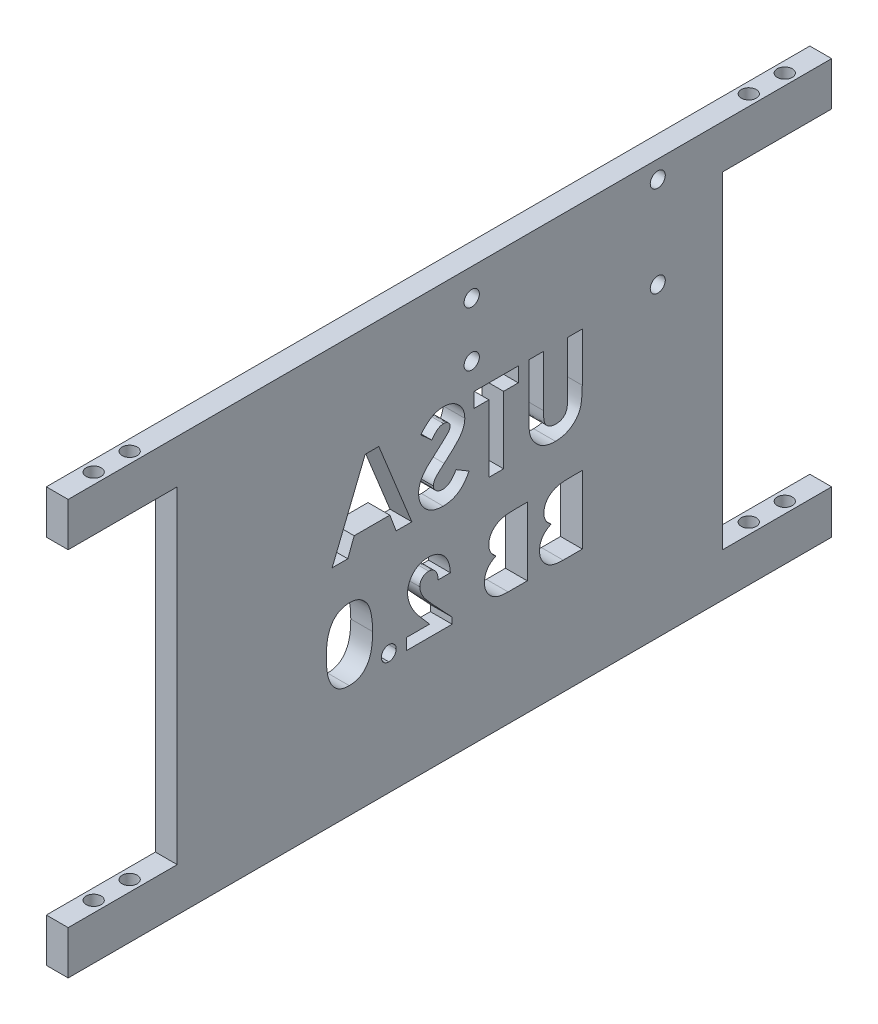
SolidWorks part; units mm, degrees
ref_plane "Front Plane" through (0, 0, 0) normal (0, 0, 1) x (1, 0, 0)
ref_plane "Top Plane" through (0, 0, 0) normal (0, 1, 0) x (1, 0, 0)
ref_plane "Right Plane" through (0, 0, 0) normal (1, 0, 0) x (0, 0, -1)
sketch "Sketch1" plane through (0, 0, 0) normal (1, 0, 0) x (0, 0, -1)
  line L0 (62.997, 20.3703) -> (88.397, 20.3703)
  line L2 (-64.003, 96.5703) -> (-64.003, 20.3703)
  line L4 (62.997, 96.5703) -> (62.997, 20.3703)
  line L6 (-89.403, 10.2103) -> (-89.403, 20.3703)
  line L7 (-89.403, 20.3703) -> (-64.003, 20.3703)
  line L8 (88.397, 10.2103) -> (88.397, 20.3703)
  line L9 (-89.403, 10.2103) -> (88.397, 10.2103)
  line L10 (-64.003, 58.4703) -> (75.8155, 58.4703) construction
  line L11 (62.997, 96.5703) -> (88.397, 96.5703)
  line L12 (88.397, 106.7303) -> (88.397, 96.5703)
  line L13 (-89.403, 106.7303) -> (88.397, 106.7303)
  line L14 (-89.403, 106.7303) -> (-89.403, 96.5703)
  line L15 (-89.403, 96.5703) -> (-64.003, 96.5703)
  dimension "D1" = 76.2
  dimension "D2" = 127
  dimension "D3" = 10.16
  dimension "D4" = 62.997
  dimension "D5" = 88.397
  dimension "D6" = 96.5703
extrude "Boss-Extrude1" add sketch "Sketch1" along normal blind 5.08
sketch "Sketch6" plane through (0, 0, 0) normal (1, 0, 0) x (0, 0, -1)
  line L0 (-64.003, 96.5703) -> (-64.003, 20.3703) construction
  text T0 "UTSA" font "Century Gothic" height in points 72
  dimension "D1" = 96.52
  dimension "D2" = 62.1931
extrude "Cut-Extrude7" cut sketch "Sketch6" along normal blind 22.86
sketch "Sketch7" plane through (0, 0, 0) normal (1, 0, 0) x (0, 0, -1)
  text T0 "BB 2.0" font "Century Gothic" height in points 60
  dimension "D1" = 32.1711
  dimension "D2" = 36.846
extrude "Cut-Extrude8" cut sketch "Sketch7" along normal blind 37.084
sketch "Sketch10" plane through (0, 0, 0) normal (0, 1, 0) x (1, 0, 0)
  line L0 (0, -0.4541) -> (55.052, -0.4541) construction
  line L1 (5.08, 88.397) -> (0, 88.397) construction
  line L2 (0, 88.397) -> (0, -89.403) construction
  circle A0 centre (2.54, 80.015) radius 1.7526
  circle A1 centre (2.54, 71.633) radius 1.7526
  circle A2 centre (2.54, -80.9233) radius 1.7526
  circle A3 centre (2.54, -72.5413) radius 1.7526
  dimension "D1" = 3.5052
  dimension "D2" = 8.382
  dimension "D3" = 8.382
  dimension "D4" = 2.54
extrude "Cut-Extrude9" cut sketch "Sketch10" against normal blind 119.38 and the other way blind 119.38
sketch "Sketch11" plane through (0, 0, 0) normal (1, 0, 0) x (0, 0, -1)
  line L0 (88.397, 106.7303) -> (-89.403, 106.7303) construction
  circle A0 centre (47.9004, 102.5825) radius 1.7526
  circle A1 centre (47.9004, 81.4166) radius 1.7526
  dimension "D1" = 3.5052
  dimension "D2" = 4.1478
  dimension "D3" = 21.1658
  dimension "D4" = 47.9004
extrude "Cut-Extrude10" cut sketch "Sketch11" along normal blind 12.954
sketch "Sketch12" plane through (0, 0, 0) normal (1, 0, 0) x (0, 0, -1)
  circle A0 centre (4.577, 100.3075) radius 1.778
  circle A1 centre (4.577, 87.6075) radius 1.778
  dimension "D1" = 3.556
extrude "Cut-Extrude11" cut sketch "Sketch12" along normal blind 28.194
sketch "Sketch13" plane through (0, 0, 0) normal (1, 0, 0) x (0, 0, -1)
  line L0 (-18.8514, 77.1471) -> (-22.5223, 69.4863)
  line L1 (-22.5223, 69.4863) -> (-17.5548, 67.106)
  line L2 (-17.5548, 67.106) -> (-14.5422, 68.2962)
  line L3 (-14.5422, 68.2962) -> (-14.5422, 73.3167)
  line L4 (-14.5422, 73.3167) -> (-18.8514, 77.1471)
  line L5 (15.6924, 50.3737) -> (15.6924, 45.1858)
  line L6 (15.6924, 45.1858) -> (15.6924, 38.2089)
  line L7 (15.6924, 38.2089) -> (11.7568, 38.2089)
  line L8 (11.7568, 38.2089) -> (8.8945, 40.3557)
  line L9 (8.8945, 40.3557) -> (8.8945, 43.7546)
  line L10 (8.8945, 43.7546) -> (12.5171, 45.1858)
  line L11 (12.5171, 45.1858) -> (10.3256, 48.3164)
  line L12 (10.3256, 48.3164) -> (11.4213, 51.2682)
  line L13 (11.4213, 51.2682) -> (15.6924, 50.3737)
  line L14 (23.3849, 50.3737) -> (24.1899, 45.8119)
  line L15 (24.1899, 45.8119) -> (21.3723, 42.0552)
  line L16 (21.3723, 42.0552) -> (23.3133, 39.2823)
  line L17 (23.3133, 39.2823) -> (27.8996, 38.3218)
  line L18 (27.8996, 38.3218) -> (28.6622, 48.0928)
  line L19 (28.6622, 48.0928) -> (28.6622, 50.3737)
  line L20 (28.6622, 50.3737) -> (23.3849, 50.3737)
  line L21 (-27.2421, 49.7923) -> (-27.2421, 42.0552)
  line L22 (-27.2421, 42.0552) -> (-24.5498, 38.2089)
  line L23 (-24.5498, 38.2089) -> (-20.4304, 38.9359)
  line L24 (-20.4304, 38.9359) -> (-20.4304, 47.7798)
  line L25 (-20.4304, 47.7798) -> (-22.4901, 50.7222)
  line L26 (-22.4901, 50.7222) -> (-25.8959, 51.4355)
  line L27 (-25.8959, 51.4355) -> (-27.2421, 49.7923)
  dimension "D1" = 8.8945
  dimension "D2" = 10.3256
  dimension "D3" = 11.4213
  dimension "D4" = 11.7568
  dimension "D5" = 12.5171
  dimension "D6" = 15.6924
  dimension "D7" = 21.3723
  dimension "D8" = 23.3133
  dimension "D9" = 23.3849
  dimension "D10" = 24.1899
  dimension "D11" = 27.8996
  dimension "D12" = 28.6622
  dimension "D13" = 14.5422
  dimension "D14" = 17.5548
  dimension "D15" = 18.8514
  dimension "D16" = 20.4304
  dimension "D17" = 22.4901
  dimension "D18" = 22.5223
  dimension "D19" = 24.5498
  dimension "D20" = 25.8959
  dimension "D21" = 27.2421
  dimension "D22" = 38.2089
  dimension "D23" = 38.3218
  dimension "D24" = 38.9359
  dimension "D25" = 39.2823
  dimension "D26" = 40.3557
  dimension "D27" = 45.1858
  dimension "D28" = 43.7546
  dimension "D29" = 47.7798
  dimension "D30" = 67.106
  dimension "D31" = 69.4863
  dimension "D32" = 48.0928
  dimension "D34" = 49.7923
  dimension "D40" = 68.2962
  dimension "D42" = 73.3167
extrude "Cut-Extrude12" cut sketch "Sketch13" along normal blind 46.482
